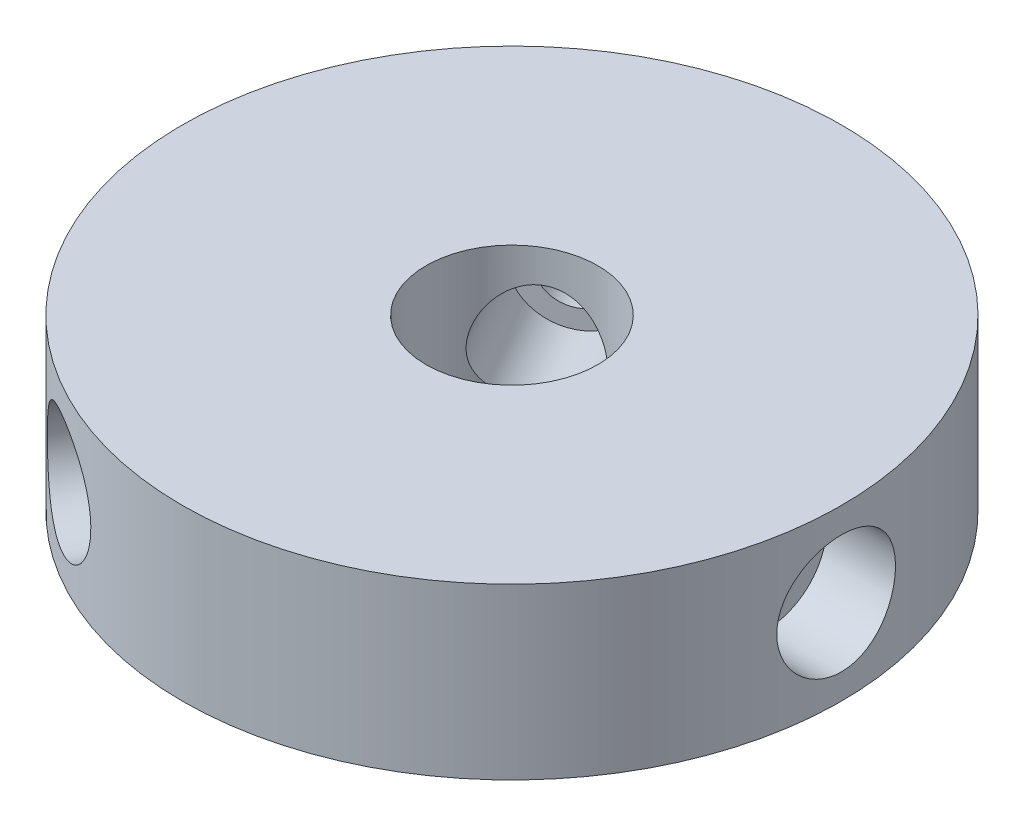
SolidWorks part; units mm, degrees
ref_plane "Front Plane" through (0, 0, 0) normal (0, 0, 1) x (1, 0, 0)
ref_plane "Top Plane" through (0, 0, 0) normal (0, 1, 0) x (1, 0, 0)
ref_plane "Right Plane" through (0, 0, 0) normal (1, 0, 0) x (0, 0, -1)
sketch "Sketch1" plane through (0, 0, 0) normal (0, 1, 0) x (1, 0, 0)
  circle A0 centre (0, 0) radius 4.05
  circle A1 centre (0, 0) radius 15.55
  point P4 (15.55, 0)
  dimension "D1" = 8.1
  dimension "D2" = 11.5
extrude "Boss-Extrude1" add sketch "Sketch1" along normal mid plane 8
ref_plane "Plane1" through (15.55, 0, 0) normal (1, 0, 0) x (0, 0, -1)
sketch "Sketch2" plane through (15.55, 0, 0) normal (1, 0, 0) x (0, 0, -1)
  circle A0 centre (0, 0) radius 2.8
  point P3 (-2.8, 0)
  point P4 (2.8, 0)
  dimension "D1" = 5.6
sketch "Sketch3" plane through (0, 0, 0) normal (0, 1, 0) x (1, 0, 0)
  line L0 (0, 0) -> (15.55, 0) construction
  line L1 (15.55, 0) -> (15.55, 2.8)
  line L2 (15.55, 2.8) -> (12.05, 2.8)
  line L3 (12.05, 2.8) -> (12.05, 1.55)
  line L4 (12.05, 1.55) -> (8.55, 1.55)
  line L5 (8.55, 1.55) -> (8.55, 2.45)
  line L6 (8.55, 2.45) -> (1.1146, 2.45)
  line L7 (1.1146, 2.45) -> (1.1146, 0)
  line L8 (1.1146, 0) -> (15.55, 0)
  circle A0 centre (0, 0) radius 4.05 construction
  point P4 (4.05, 0)
  point P5 (12.05, 0)
  point P8 (1.1146, 0)
  dimension "D1" = 8
  dimension "D2" = 2.45
  dimension "D3" = 4.5
  dimension "D4" = 1.55
revolve "Cut-Revolve1" cut sketch "Sketch3" angle 360 about L0
sketch "Sketch5" plane through (0, 0, 0) normal (0, 0, 1) x (1, 0, 0)
  line L0 (0, -6.8412) -> (0, 6.8412) construction
  point P2 (0, 0)
pattern_circular "CirPattern1" count 3 over 360 about axis through (0, 0, 0) along (0, 1, 0) of "Cut-Revolve1"
